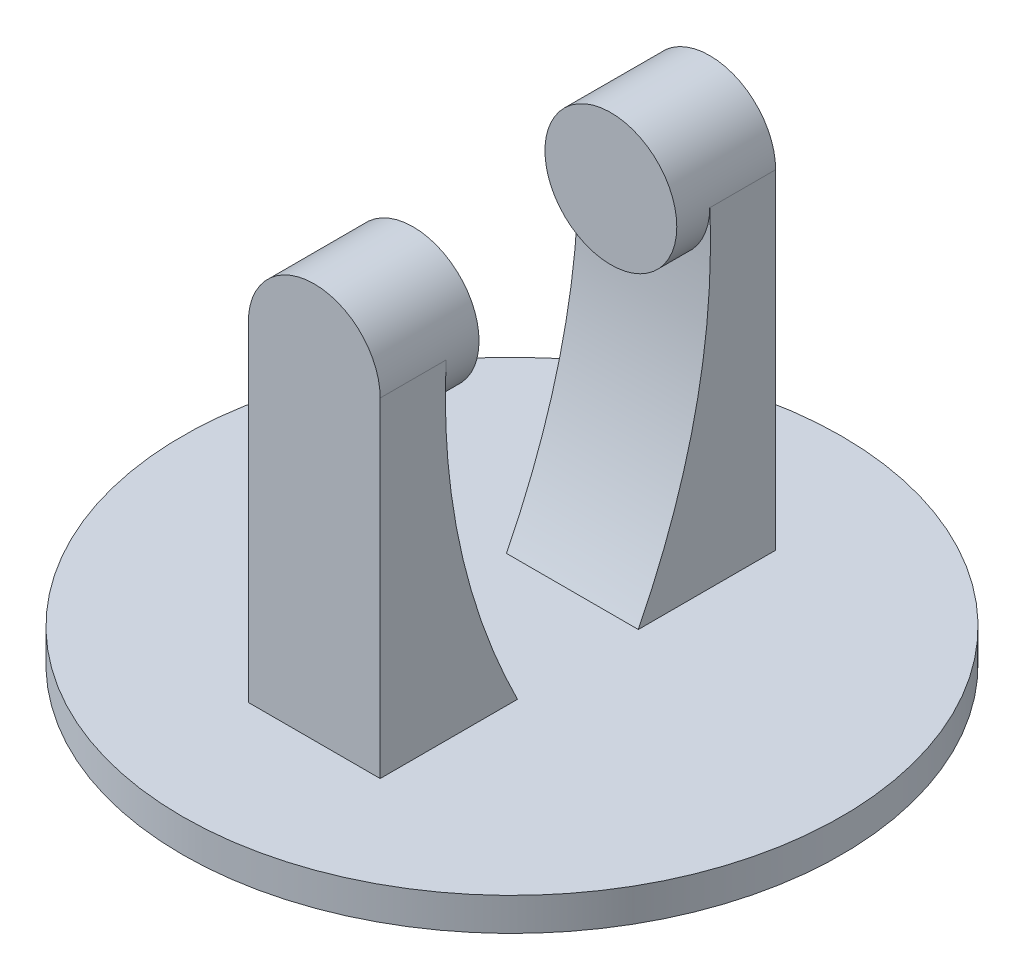
SolidWorks part; units mm, degrees
ref_plane "Front Plane" through (0, 0, 0) normal (0, 0, 1) x (1, 0, 0)
ref_plane "Top Plane" through (0, 0, 0) normal (0, 1, 0) x (1, 0, 0)
ref_plane "Right Plane" through (0, 0, 0) normal (1, 0, 0) x (0, 0, -1)
sketch "Sketch2" plane through (0, 0, 0) normal (0, 1, 0) x (1, 0, 0)
  circle A0 centre (0, 0) radius 50
extrude "Boss-Extrude1" add sketch "Sketch2" along normal blind 5
sketch "Sketch3" plane through (0, 5, 0) normal (0, 1, 0) x (1, 0, 0)
  line L1 (-30, 30) -> (30, 30)
  line L2 (-30, 30) -> (-30, -30)
  line L3 (-30, -30) -> (30, -30)
  line L4 (30, 30) -> (30, -30)
  line L5 (-30, 30) -> (30, -30) construction
  line L6 (-30, -30) -> (30, 30) construction
  point P0 (0, 0)
extrude "Boss-Extrude2" add sketch "Sketch3" along normal blind 60
sketch "Sketch19" plane through (0, 0, 30) normal (0, 0, 1) x (1, 0, 0)
  line L1 (-30, 65) -> (30, 65) construction
  line L3 (-10, 55) -> (-10, 5)
  line L4 (10, 55) -> (10, 5)
  line L5 (-10, 5) -> (-30, 5)
  line L6 (-30, 5) -> (-30, 65)
  line L7 (-30, 65) -> (0, 65)
  arc A0 (0, 65) -> (-10, 55) centre (0, 55) ccw
  arc A1 (0, 65) -> (10, 55) centre (0, 55) cw
  line M3 (-30, 5) -> (30, 5)
  line M5 (30, 65) -> (-30, 65)
  line M6 (-30, 65) -> (-30, 5)
extrude "Cut-Extrude14" cut sketch "Sketch19" against normal blind 150 contours A0 L3 M5 M6 M3
sketch "Sketch29" plane through (0, 0, 30) normal (0, 0, 1) x (1, 0, 0)
  line L0 (0, 65) -> (30, 65)
  line L1 (30, 65) -> (30, 5)
  line L2 (30, 5) -> (10, 5)
  line L3 (-10, 5) -> (30, 5) construction
  line L4 (10, 5) -> (10, 55)
  circle A0 centre (0, 55) radius 10
  arc A1 (10, 55) -> (0, 65) centre (0, 55) ccw
  line M3 (-10, 5) -> (30, 5)
  line M4 (30, 5) -> (30, 65)
  line M5 (30, 65) -> (0, 65)
extrude "Cut-Extrude15" cut sketch "Sketch29" against normal blind 150 contours A0 L4 M3 M4 M5
sketch "Sketch30" plane through (0, 0, 0) normal (1, 0, 0) x (0, 0, -1)
  line L0 (0, 65) -> (0, 5) construction
  line L1 (30, 65) -> (-30, 65) construction
  line L2 (50, 5) -> (-50, 5) construction
  line L3 (20, 65) -> (-20, 65)
  line L4 (-20, 65) -> (-20, 55)
  line L5 (30, 55) -> (-30, 55) construction
  line L6 (-9.1662, 5) -> (9.1662, 5)
  line L7 (20, 65) -> (20, 55)
  spline S0 degree 2 poles (-20, 55) (-21.2181, 29.1291) (-9.1662, 5) knots 0 0 0 1 1 1
  spline S1 degree 2 poles (20, 55) (21.2181, 29.1291) (9.1662, 5) knots 0 0 0 1 1 1
extrude "Cut-Extrude16" cut sketch "Sketch30" against normal blind 56 and the other way blind 71
sketch "Sketch31" plane through (0, 0, 20) normal (0, 0, -1) x (-1, 0, 0)
  circle A0 centre (0, 55) radius 10
extrude "Boss-Extrude5" add sketch "Sketch31" along normal blind 5
sketch "Sketch32" plane through (0, 0, -20) normal (0, 0, 1) x (1, 0, 0)
  circle A0 centre (0, 55) radius 10
extrude "Boss-Extrude6" add sketch "Sketch32" along normal blind 5
